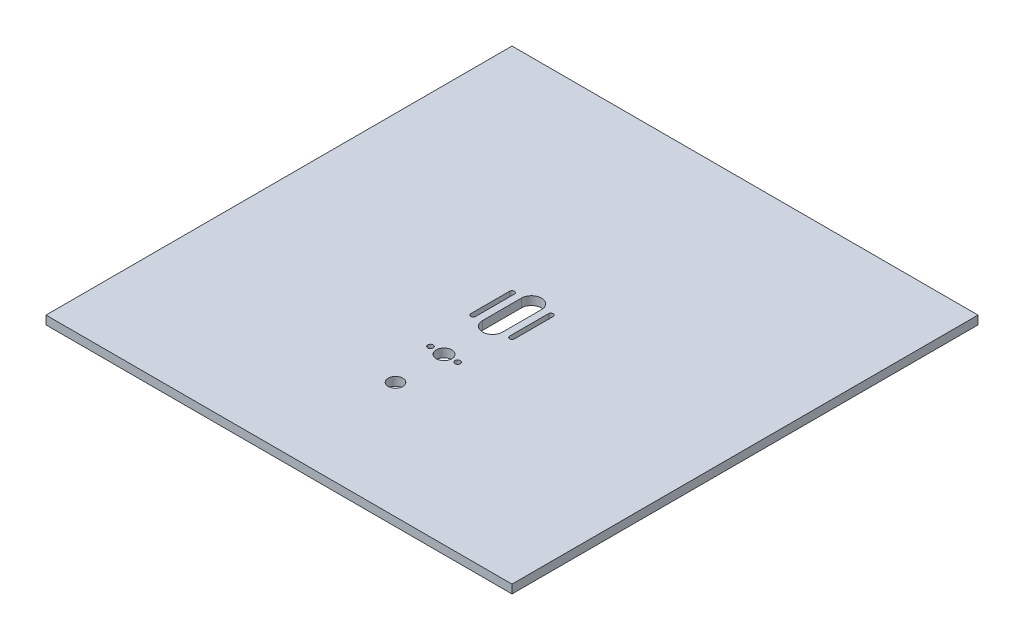
SolidWorks part; units mm, degrees
ref_plane "Front Plane" through (0, 0, 0) normal (0, 0, 1) x (1, 0, 0)
ref_plane "Top Plane" through (0, 0, 0) normal (0, 1, 0) x (1, 0, 0)
ref_plane "Right Plane" through (0, 0, 0) normal (1, 0, 0) x (0, 0, -1)
sketch "Sketch1" plane through (0, 0, 0) normal (0, 1, 0) x (1, 0, 0)
  line L1 (-152.4, -152.4) -> (152.4, -152.4)
  line L2 (-152.4, -152.4) -> (-152.4, 152.4)
  line L3 (-152.4, 152.4) -> (152.4, 152.4)
  line L4 (152.4, -152.4) -> (152.4, 152.4)
  line L5 (-152.4, -152.4) -> (152.4, 152.4) construction
  line L6 (-152.4, 152.4) -> (152.4, -152.4) construction
  point P0 (0, 0)
  dimension "D1" = 304.8
  dimension "D2" = 304.8
extrude "Boss-Extrude1" add sketch "Sketch1" along normal blind 5.588
sketch "Sketch2" plane through (0, 5.588, 0) normal (0, 1, 0) x (1, 0, 0)
  line L0 (-8.89, -44.45) -> (8.89, -44.45) construction
  line L1 (0, -76.2) -> (0, 0) construction
  line L2 (0, 12.7) -> (0, -12.7) construction
  line L3 (6.5405, 12.7) -> (6.5405, -12.7)
  line L4 (-6.5405, 12.7) -> (-6.5405, -12.7)
  line L5 (-12.7, 12.7) -> (-12.7, -12.7) construction
  line L6 (-12.7, -12.7) -> (12.7, -12.7) construction
  line L7 (-12.7, -12.7) -> (-12.7, 12.7) construction
  line L8 (-12.7, 12.7) -> (12.7, 12.7) construction
  line L9 (12.7, -12.7) -> (12.7, 12.7) construction
  line L10 (-12.7, -12.7) -> (12.7, 12.7) construction
  line L11 (-12.7, 12.7) -> (12.7, -12.7) construction
  line L12 (-11.1125, 12.7) -> (-11.1125, -12.7)
  line L13 (-14.2875, 12.7) -> (-14.2875, -12.7)
  line L14 (12.7, 12.7) -> (12.7, -12.7) construction
  line L15 (14.2875, 12.7) -> (14.2875, -12.7)
  line L16 (11.1125, 12.7) -> (11.1125, -12.7)
  circle A0 centre (0, -76.2) radius 4.7625
  circle A1 centre (0, -44.45) radius 5.08
  circle A2 centre (-8.89, -44.45) radius 1.778
  circle A3 centre (8.89, -44.45) radius 1.778
  arc A4 (6.5405, 12.7) -> (-6.5405, 12.7) centre (0, 12.7) ccw
  arc A5 (-6.5405, -12.7) -> (6.5405, -12.7) centre (0, -12.7) ccw
  arc A6 (-11.1125, 12.7) -> (-14.2875, 12.7) centre (-12.7, 12.7) ccw
  arc A7 (-14.2875, -12.7) -> (-11.1125, -12.7) centre (-12.7, -12.7) ccw
  arc A8 (14.2875, 12.7) -> (11.1125, 12.7) centre (12.7, 12.7) ccw
  arc A9 (11.1125, -12.7) -> (14.2875, -12.7) centre (12.7, -12.7) ccw
  point P7 (0, -44.45)
  point P10 (0, 0)
  point P21 (-12.7, 0)
  point P26 (12.7, 0)
  dimension "D1" = 10.16
  dimension "D2" = 3.556
  dimension "D10" = 9.525
  dimension "D3" = 8.89
  dimension "D4" = 31.75
  dimension "D5" = 13.081
  dimension "D6" = 3.175
  dimension "D7" = 25.4
  dimension "D8" = 44.45
  dimension "D9" = 25.4
extrude "Cut-Extrude1" cut sketch "Sketch2" against normal through all
